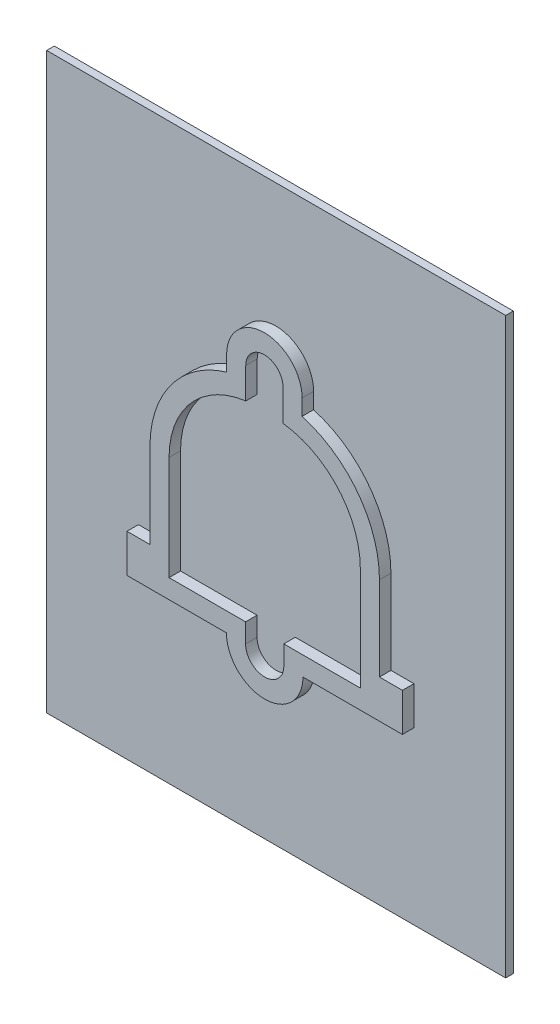
SolidWorks part; units mm, degrees
ref_plane "Face" through (0, 0, 0) normal (0, 0, 1) x (1, 0, 0)
ref_plane "Dessus" through (0, 0, 0) normal (0, 1, 0) x (1, 0, 0)
ref_plane "Droite" through (0, 0, 0) normal (1, 0, 0) x (0, 0, -1)
sketch "Esquisse1" plane through (0, 0, 0) normal (0, 0, 1) x (1, 0, 0)
  line L0 (-12.8328, 25.0214) -> (-12.8328, 25.4375)
  line L5 (-14.806, 25.0375) -> (-14.806, 25.4375)
  line L6 (-16.8104, 20.1316) -> (-17.4104, 20.1316)
  line L7 (-14.8104, 19.1316) -> (-17.4104, 19.1316)
  line L8 (-16.8104, 22.3529) -> (-16.8104, 20.1316)
  line L9 (-10.8104, 22.3316) -> (-10.8104, 20.1316)
  line L10 (-10.2104, 19.1316) -> (-10.2104, 20.1316)
  line L11 (-17.4104, 19.1316) -> (-17.4104, 20.1316)
  line L12 (-10.2104, 20.1316) -> (-10.8104, 20.1316)
  line L13 (-10.2104, 19.1316) -> (-12.8104, 19.1316)
  line L14 (-11.3104, 22.3316) -> (-11.3104, 19.6316)
  line L15 (-11.3104, 19.6316) -> (-13.3104, 19.6316)
  line L16 (-16.3104, 22.3529) -> (-16.3104, 19.6316)
  line L17 (-14.306, 24.6339) -> (-14.306, 25.4375)
  line L18 (-13.3328, 24.6147) -> (-13.3328, 25.4375)
  line L19 (-14.3104, 19.1316) -> (-14.3104, 19.6316)
  line L20 (-13.3104, 19.1316) -> (-13.3104, 19.6316)
  line L21 (-14.3104, 19.6316) -> (-16.3104, 19.6316)
  arc A0 (-16.3338, 23.9155) -> (-14.806, 25.0375) centre (-14.0104, 22.3529) cw
  arc A1 (-12.8104, 19.1316) -> (-14.8104, 19.1316) centre (-13.8104, 19.1316) cw
  arc A2 (-14.806, 25.4375) -> (-12.8328, 25.4375) centre (-13.8194, 25.4375) cw
  arc A3 (-16.8104, 22.3529) -> (-16.3338, 23.9155) centre (-14.0104, 22.3529) cw
  arc A4 (-10.8104, 22.3316) -> (-12.8328, 25.0214) centre (-13.6104, 22.3316) ccw
  arc A5 (-16.3104, 22.3529) -> (-15.9189, 23.6365) centre (-14.0104, 22.3529) cw
  arc A6 (-15.9189, 23.6365) -> (-14.306, 24.6339) centre (-14.0104, 22.3529) cw
  arc A7 (-14.306, 25.4375) -> (-13.3328, 25.4375) centre (-13.8194, 25.4375) cw
  arc A8 (-11.3104, 22.3316) -> (-13.3328, 24.6147) centre (-13.6104, 22.3316) ccw
  arc A9 (-13.3104, 19.1316) -> (-14.3104, 19.1316) centre (-13.8104, 19.1316) cw
  dimension "D2" = 1
extrude "Extrusion3" add sketch "Esquisse1" along normal blind 0.3
sketch "Esquisse2" plane through (0, 0, 0) normal (0, 0, -1) x (-1, 0, 0)
  line L0 (13.8104, 25.306) -> (13.8104, 15.8215) construction
  line L1 (7.8104, 29.6677) -> (7.8104, 14.6677)
  line L2 (7.8104, 29.6677) -> (19.8104, 29.6677)
  line L3 (7.8104, 14.6677) -> (19.8104, 14.6677)
  line L6 (19.8104, 29.6677) -> (19.8104, 14.6677)
  dimension "D1" = 12
extrude "Extrusion4" add sketch "Esquisse2" along normal blind 0.2
